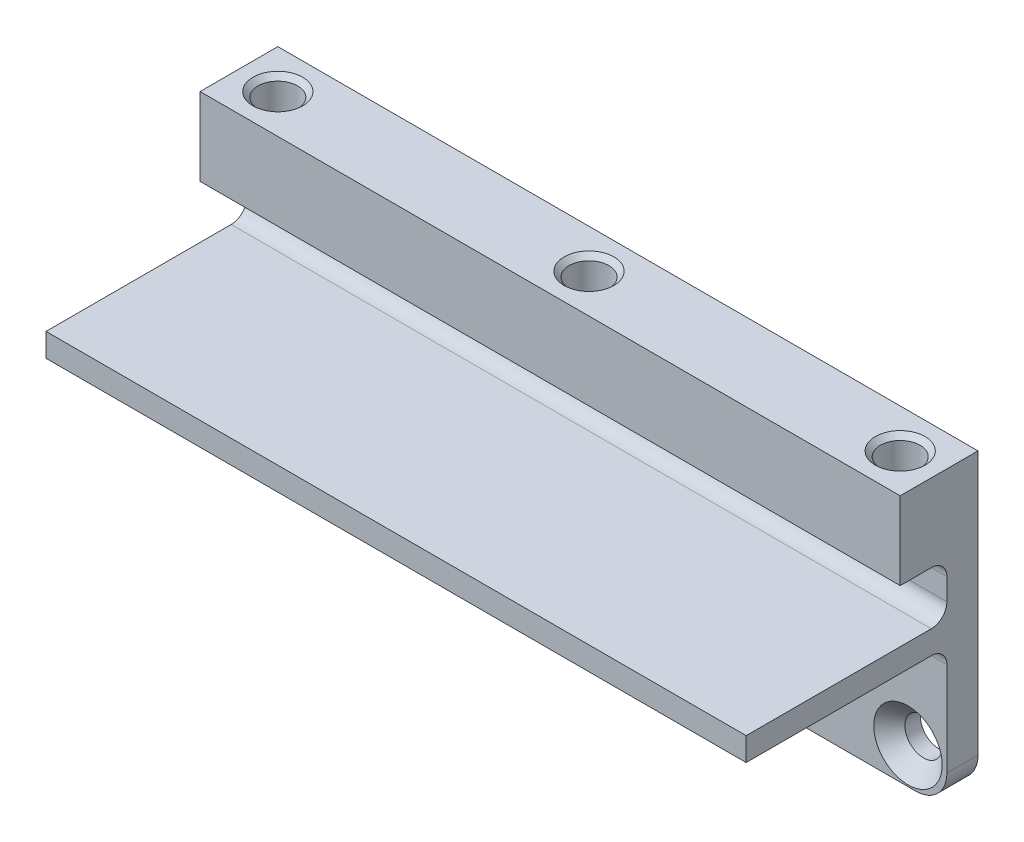
SolidWorks part; units mm, degrees
ref_plane "Front" through (0, 0, 0) normal (0, 0, 1) x (1, 0, 0)
ref_plane "Top" through (0, 0, 0) normal (0, 1, 0) x (1, 0, 0)
ref_plane "Right" through (0, 0, 0) normal (1, 0, 0) x (0, 0, -1)
sketch "Sketch1" plane through (0, 0, 0) normal (1, 0, 0) x (0, 0, -1)
  line L0 (0, 0) -> (0, 18.94)
  line L1 (0, 50) -> (0, -50) construction
  line L2 (0, 18.94) -> (-5, 18.94)
  line L3 (-5, 18.94) -> (-5, 13.94)
  line L4 (-5, 13.94) -> (-2, 13.94)
  line L5 (-2, 13.94) -> (-2, 10.54)
  line L6 (-2, 10.54) -> (-14.9, 10.54)
  line L7 (-14.9, 10.54) -> (-14.9, 9.04)
  line L8 (-14.9, 9.04) -> (-2, 9.04)
  line L9 (-2, 9.04) -> (-2, 0)
  line L10 (50, 0) -> (-50, 0) construction
  line L11 (-2, 0) -> (0, 0)
  dimension "D1" = 18.94
  dimension "D2" = 14.9
  dimension "D3" = 2
  dimension "D4" = 5
  dimension "D5" = 1.5
  dimension "D6" = 5
  dimension "D7" = 8.4
extrude "Boss-Extrude1" add sketch "Sketch1" along normal mid plane 45
fillet "Fillet1" radius 1 3 edges at (0, 10.54, 2) (0, 9.04, 2) (0, 13.94, 2)
hole_wizard "CSK for M2 Flat Head Machine Screw1" positions "Sketch4" profile "Sketch3" countersink size "M2" standard "ANSI Metric"
sketch "Sketch4" plane through (0, 0, 2) normal (0, 0, 1) x (1, 0, 0)
  line L0 (-22.5, 2.3) -> (22.5, 2.3) construction
  line L1 (-22.5, 8.04) -> (-22.5, 0) construction
  line L2 (22.5, 8.04) -> (22.5, 0) construction
  line L3 (22.5, 0) -> (-22.5, 0) construction
  point P10 (-20, 2.3)
  point P12 (0, 2.3)
  point P14 (20, 2.3)
  dimension "D1" = 20
  dimension "D2" = 20
  dimension "D3" = 2.3
sketch "Sketch3" plane through (20, 2.3, 2) normal (1, 0, 0) x (0, -1, 0)
  line L0 (0, 0) -> (0, 7.171)
  line L1 (0, 7.171) -> (1.2, 6.45)
  line L2 (1.2, 6.45) -> (1.2, 1)
  line L3 (1.2, 1) -> (2.2, 0)
  line L5 (2.2, 0) -> (0, 0)
  line L6 (-1.2, 1) -> (-2.2, 0) construction
  line L10 (0, 7.171) -> (-1.2, 6.45) construction
  line L11 (0, -6.35) -> (0, 107.95) construction
  dimension "Hole Dia." = 2.4
  dimension "Hole Depth" = 6.45
  dimension "Near C'Sink Dia." = 4.4
  dimension "Near C'Sink Angle" = 90
  dimension "Drill Angle" = 118
fillet "Fillet2" radius 2 2 edges at (-22.5, 0, 1) (22.5, 0, 1)
hole_wizard "Tapped Hole for M2.5x0.45 Helicoil1" positions "Sketch5" profile "Sketch6" tap size "M2.5x0.45" standard "Helicoil® Metric"
sketch "Sketch5" plane through (0, 18.94, 0) normal (0, 1, 0) x (1, 0, 0)
  line L0 (-22.5, -2.5) -> (22.5, -2.5) construction
  line L1 (-22.5, 0) -> (-22.5, -5) construction
  line L2 (22.5, 0) -> (22.5, -5) construction
  point P10 (-20, -2.5)
  point P12 (0, -2.5)
  point P14 (20, -2.5)
  point P20 (0, 0)
  dimension "D1" = 20
  dimension "D2" = 20
cosmetic thread "Hole Thread1" parameters "D1"=4, "D2"=3.145
cosmetic thread "Hole Thread2" parameters "D1"=4, "D2"=3.145
cosmetic thread "Hole Thread3" parameters "D1"=4, "D2"=3.145
sketch "Sketch6" plane through (20, 18.94, 2.5) normal (1, 0, 0) x (0, 0, 1)
  line L0 (0, 0) -> (0, 4.7661)
  line L1 (0, 4.7661) -> (1.275, 4)
  line L2 (1.275, 4) -> (1.275, 0.3225)
  line L3 (1.275, 0.3225) -> (1.5975, 0)
  line L5 (1.5975, 0) -> (0, 0)
  line L6 (-1.275, 0.3225) -> (-1.5975, 0) construction
  line L10 (0, 4.7661) -> (-1.275, 4) construction
  line L11 (0, -6.35) -> (0, 107.95) construction
  dimension "Tap Drill Dia." = 2.55
  dimension "Tap Drill Depth" = 4
  dimension "Near C'Sink Dia." = 3.195
  dimension "Near C'Sink Angle" = 90
  dimension "Drill Angle" = 118
